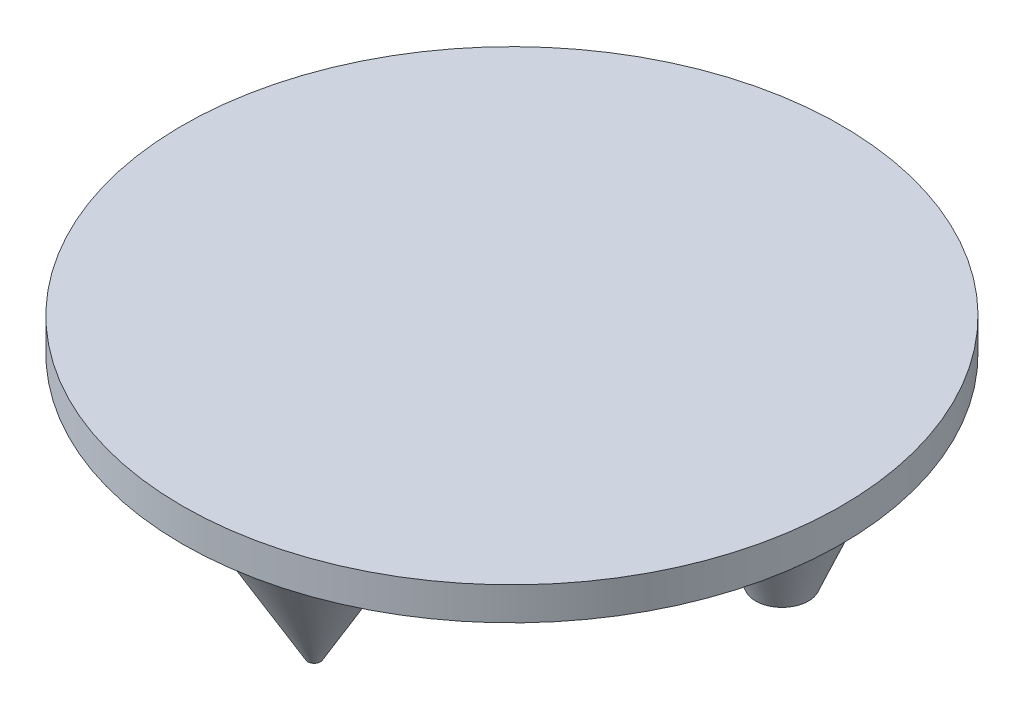
SolidWorks part; units mm, degrees
ref_plane "Front Plane" through (0, 0, 0) normal (0, 0, 1) x (1, 0, 0)
ref_plane "Top Plane" through (0, 0, 0) normal (0, 1, 0) x (1, 0, 0)
ref_plane "Right Plane" through (0, 0, 0) normal (1, 0, 0) x (0, 0, -1)
other "Bounding Box"
ref_plane "Default Plane" through (-10.3017, -6.35, 14.7124) normal (-0.1736, 0, -0.9848) x (-0.9848, 0, 0.1736)
sketch "Sketch2" plane through (0, 0, 0) normal (0, 1, 0) x (1, 0, 0)
  circle A0 centre (0, 0) radius 12.7
  dimension "D1" = 25.4
extrude "Boss-Extrude1" add sketch "Sketch2" along normal blind 1.27
sketch "Sketch3" plane through (0, 0, 0) normal (0, -1, 0) x (1, 0, 0)
  circle A0 centre (0, 7.62) radius 3.175
  dimension "D1" = 6.35
  dimension "D2" = 7.62
extrude "Boss-Extrude2" add sketch "Sketch3" along normal blind 6.35
pattern_circular "CirPattern1" count 3 over 360 about axis through (0, 0, 0) along (0, 1, 0) of "Boss-Extrude2"
chamfer "Chamfer1" distance 5.08 angle 30 1 edges at (0, -6.35, 4.445)
chamfer "Chamfer2" distance 5.08 angle 23 1 edges at (3.8495, -6.35, -2.2225)
chamfer "Chamfer3" distance 5.08 angle 16 1 edges at (-3.8495, -6.35, -2.2225)
fillet "Fillet1" radius 2.54 3 edges at (6.5991, -1.27, -6.985) (0, -1.27, 4.445) (-6.5991, -1.27, -6.985)
